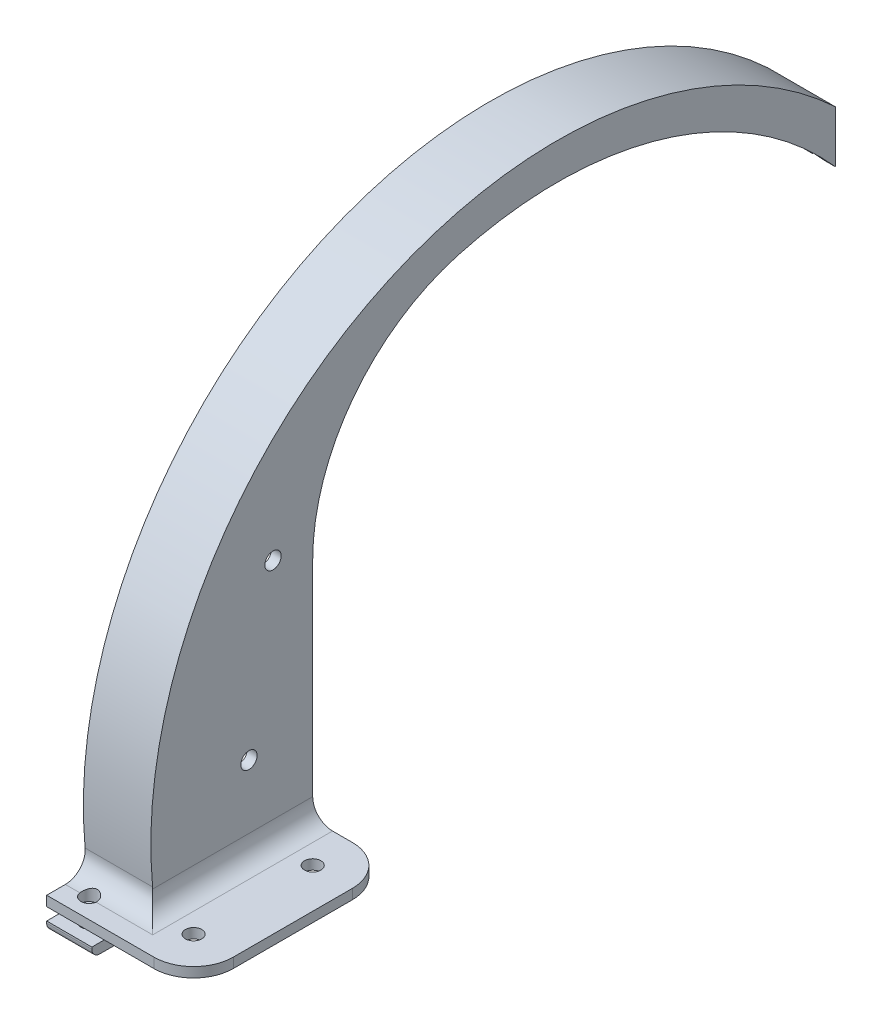
SolidWorks part; units mm, degrees
ref_plane "Alzado" through (0, 0, 0) normal (0, 0, 1) x (1, 0, 0)
ref_plane "Planta" through (0, 0, 0) normal (0, 1, 0) x (1, 0, 0)
ref_plane "Vista lateral" through (0, 0, 0) normal (1, 0, 0) x (0, 0, -1)
sketch "Croquis1" plane through (0, 0, 0) normal (1, 0, 0) x (0, 0, -1)
  line L0 (-100.8938, -17.44) -> (-91.625, -17.44)
  line L1 (70, 74.7242) -> (70, 61.6384)
  circle A0 centre (0, 0) radius 93.27
  circle A1 centre (0, 0) radius 102.39
  dimension "D2" = 93.27
  dimension "D1" = 9.12
  dimension "D3" = 70
  dimension "D4" = 17.44
extrude "Saliente-Extruir1" add sketch "Croquis1" along normal blind 17 contours L1 A1 L0 A0
sketch "Croquis5" plane through (0, 0, 0) normal (-1, 0, 0) x (0, 0, 1)
  line L0 (-70, 74.7242) -> (-70, 61.6384) construction
  line L1 (100.8938, -17.44) -> (91.625, -17.44) construction
  line L2 (-70, 71.176) -> (-70, 65.3597)
  line L3 (98.2948, -17.44) -> (94.1687, -17.44)
  arc A0 (94.1687, -17.44) -> (-70, 65.3597) centre (0, 0) ccw
  arc A1 (98.2948, -17.44) -> (-70, 71.176) centre (0, 0) ccw
  circle A5 centre (0, 0) radius 93.27 construction
  point P6 (140.7387, -10.2801)
  dimension "D2" = 2.5
  dimension "D1" = 4.06
extrude "Cortar-Extruir1" cut sketch "Croquis5" against normal blind 8.88
sketch "Croquis6" plane through (17, 0, 0) normal (1, 0, 0) x (0, 0, -1)
  circle A0 centre (0, 0) radius 93.27
  circle A1 centre (0, 0) radius 99.89
  circle A2 centre (0, 0) radius 93.27 construction
  circle A3 centre (0, 0) radius 102.39 construction
  point P0 (0, 0)
  dimension "D1" = 2.5
extrude "Cortar-Extruir2" cut sketch "Croquis6" against normal blind 3.12 from offset 2.5 offset against normal yes
sketch "Croquis2" plane through (17, 0, 0) normal (1, 0, 0) x (0, 0, -1)
  line L1 (1.6483, -0.0538) -> (-100.8938, -0.0538) construction
  line L2 (-100.8938, -0.0538) -> (-100.8938, -17.44) construction
  line L4 (-111.625, -14.94) -> (-111.625, -17.44)
  line L5 (-111.625, -17.44) -> (-100.8938, -17.44)
  line L6 (-111.625, -14.94) -> (-101.2942, -14.94)
  line L9 (70, 61.6384) -> (70, 74.7242)
  line L10 (-100.8938, -17.44) -> (-91.625, -17.44)
  arc A7 (70, 74.7242) -> (-100.8938, -17.44) centre (0, 0) ccw
  arc A8 (70, 61.6384) -> (-91.625, -17.44) centre (0, 0) ccw
  arc A9 (-101.2942, -14.94) -> (-100.8938, -17.44) centre (0, 0) ccw
  point P1 (0, 0)
  point P3 (-102.178, -17.44)
  point P4 (-100.894, -17.44)
  point P5 (-103.7022, -14.8862)
  point P8 (0, 0)
  dimension "D1" = 20
  dimension "D2" = 2.5
  dimension "D3" = 0
extrude "Saliente-Extruir3" add sketch "Croquis2" against normal through all
sketch "Croquis3" plane through (17, 0, 0) normal (1, 0, 0) x (0, 0, -1)
  line L0 (-91.625, -17.44) -> (-91.625, -21.06)
  line L1 (-93.625, -23.06) -> (-109.625, -23.06)
  line L2 (-111.625, -21.06) -> (-111.625, -20.56)
  line L3 (-111.625, -20.56) -> (-100.8938, -20.56)
  line L4 (-100.8938, -20.56) -> (-100.8938, -17.44)
  line L5 (-111.625, -17.44) -> (-91.625, -17.44) construction
  line L6 (-100.8938, -17.44) -> (-91.625, -17.44)
  arc A0 (-91.625, -21.06) -> (-93.625, -23.06) centre (-93.625, -21.06) cw
  arc A1 (-109.625, -23.06) -> (-111.625, -21.06) centre (-109.625, -21.06) cw
  point P10 (0, 0)
  point P16 (0, 0)
  dimension "D3" = 2
  dimension "D1" = 3.12
  dimension "D2" = 2.5
extrude "Saliente-Extruir4" add sketch "Croquis3" against normal up to surface (11.38 mm away) from offset 5.62 up to face at (0, 53.8371, 26.7538) offset against normal yes
sketch "Croquis4" plane through (17, 0, 0) normal (1, 0, 0) x (0, 0, -1)
  line L0 (-61.625, 70.0118) -> (-61.625, -17.44)
  line L1 (-61.625, -17.44) -> (-91.625, -17.44)
  line L7 (70, 61.6384) -> (70, 74.7242)
  line L8 (-111.625, -17.44) -> (-91.625, -17.44)
  line L22 (-111.625, -14.94) -> (-111.625, -17.44)
  line L28 (-101.2942, -14.94) -> (-111.625, -14.94)
  arc A5 (70, 74.7242) -> (-101.2942, -14.94) centre (0, 0) ccw
  arc A9 (70, 61.6384) -> (-91.625, -17.44) centre (0, 0) ccw
  arc A14 (-61.625, 70.0118) -> (-91.625, -17.44) centre (0, 0) ccw
  point P6 (-100.8935, -17.4415)
  point P8 (-55.3182, 75.0945)
  point P10 (-91.344, -18.8564)
  dimension "D1" = 0
extrude "Saliente-Extruir5" add sketch "Croquis4" against normal blind 2.5
fillet "Redondeo1" radius 50 1 edges at (15.75, 70.0118, 61.625)
sketch "Croquis7" plane through (0, -17.44, 0) normal (0, -1, 0) x (1, 0, 0)
  line L1 (17, 111.625) -> (27, 111.625)
  line L2 (17, 111.625) -> (17, 61.625)
  line L3 (17, 61.625) -> (27, 61.625)
  line L4 (37, 101.625) -> (37, 71.625)
  line L5 (17, 111.625) -> (37, 61.625) construction
  line L6 (17, 61.625) -> (37, 111.625) construction
  circle A0 centre (27, 101.625) radius 2.06
  circle A1 centre (27, 71.625) radius 2.06
  arc A2 (27, 61.625) -> (37, 71.625) centre (27, 71.625) ccw
  arc A3 (27, 111.625) -> (37, 101.625) centre (27, 101.625) cw
  point P4 (27, 86.625)
  point P10 (0, 0)
  point P17 (0, 0)
  point P18 (0, 0)
  dimension "D3" = 4.12
  dimension "D4" = 10
  dimension "D5" = 10
  dimension "D7" = 10
  dimension "D1" = 50
  dimension "D2" = 20
  dimension "D6" = 10
extrude "Saliente-Extruir6" add sketch "Croquis7" against normal blind 2.5
fillet "Redondeo7" radius 5 2 edges at (8.5, -14.94, 101.2942) (17, -14.94, 81.4596)
sketch "Croquis8" plane through (0, -23.06, 0) normal (0, -1, 0) x (1, 0, 0)
  line L1 (0, 109.625) -> (11.38, 109.625) construction
  circle A0 centre (5.69, 106.625) radius 2.06
  point P2 (0, 0)
  point P6 (5.69, 109.625)
  dimension "D1" = 4.12
  dimension "D2" = 5
extrude "Cortar-Extruir3" cut sketch "Croquis8" against normal through all
sketch "Croquis9" plane through (14.5, 0, 0) normal (-1, 0, 0) x (0, 0, 1)
  line L0 (61.625, -9.94) -> (61.625, 41.6792) construction
  circle A0 centre (77.685, 6.06) radius 2.06
  circle A1 centre (71.625, 46.5745) radius 2.06
  point P4 (70.625, 46.5745)
  point P8 (44.7874, -19.5808)
  dimension "D1" = 4.12
  dimension "D2" = 14
  dimension "D3" = 16
  dimension "D4" = 10
extrude "Cortar-Extruir4" cut sketch "Croquis9" against normal through all
equation "\"D1@Croquis1\"=((\"GROSOR_PARED_IMPRESION\"+\"TOLERANCIA\")*2)+\"policarbonato\""
equation "\"venesta\"= 4'grosor de la venesta"
equation "\"policarbonato\"= 4'grosor del policarbonato"
equation "\"carton_trupan\"= 3'grosor del carton trupan caso laser"
equation "\"ancho_tot\"= 310'ancho tot sin llantas"
equation "\"largo_tot\"= 400'largo tot sin camera"
equation "\"alto_estimado\"= 300'alto estimado sin lidar"
equation "\"altoparaqpaselabotella\"= 75'alto estimado para que encaje la botella"
equation "\"alturaruedaloca\"= 22"
equation "\"anchoruedaloca\"= 35"
equation "\"anchopiso1motorybaterias\"= 150"
equation "\"dist-pisorampa\"= 5"
equation "\"anchoultimopiso\"= 170"
equation "\"paredtrasera\"= 100"
equation "\"agarradorcanasta\"= 275'recolector"
equation "\"alturapiso1y2\"= 80"
equation "\"alturapiso2y3\"= 80"
equation "\"GROSOR_PARED_IMPRESION\"=2.5"
equation "\"TOLERANCIA\"= 0.06"
equation "\"apertura\"= 70"
equation "\"D2@Croquis1\"=(4-0.02)+ ( \"TOLERANCIA\" * 2 ) + 89.17"
equation "\"D4@Croquis1\"=17.5-\"TOLERANCIA\""
equation "\"D1@Croquis3\"=\"TOLERANCIA\"+\"carton_trupan\"+\"TOLERANCIA\""
equation "\"D2@Croquis3\"=\"GROSOR_PARED_IMPRESION\""
equation "\"¡\"=160"
equation "\"D1@Croquis5\"=\"policarbonato\"+\"TOLERANCIA\""
equation "\"D2@Croquis5\"=\"GROSOR_PARED_IMPRESION\""
equation "\"D1@Croquis6\"=\"GROSOR_PARED_IMPRESION\""
equation "\"D1@Cortar-Extruir2\"=\"TOLERANCIA\"+\"carton_trupan\"+\"TOLERANCIA\""
equation "\"D1@Saliente-Extruir5\"=\"GROSOR_PARED_IMPRESION\""
